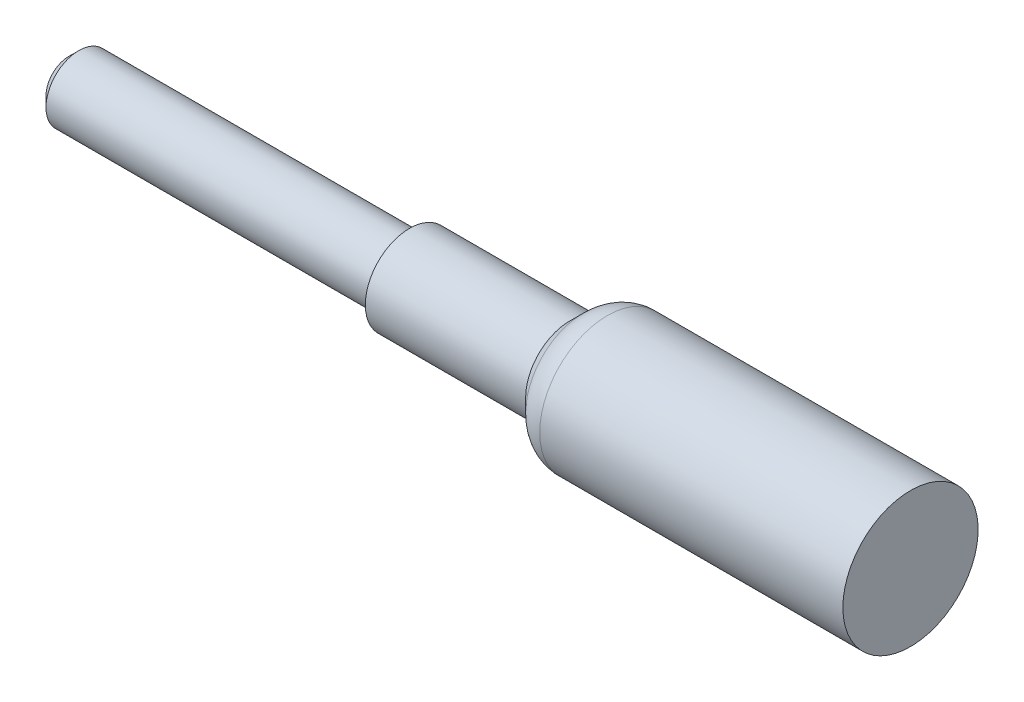
SolidWorks part; units mm, degrees
ref_plane "Front Plane" through (0, 0, 0) normal (0, 0, 1) x (1, 0, 0)
ref_plane "Top Plane" through (0, 0, 0) normal (0, 1, 0) x (1, 0, 0)
ref_plane "Right Plane" through (0, 0, 0) normal (1, 0, 0) x (0, 0, -1)
sketch "Sketch1" plane through (0, 0, 0) normal (0, 0, 1) x (1, 0, 0)
  line L0 (0, 0) -> (63.1616, 0) construction
  line L1 (31.75, 0) -> (31.75, 4.2862)
  line L2 (31.75, 4.2862) -> (11.6462, 4.2862)
  line L3 (11.6462, 4.2862) -> (10.16, 2.8)
  line L4 (10.16, 2.8) -> (0, 2.8)
  line L5 (0, 2.8) -> (0, 0)
  line L6 (0, 0) -> (31.75, 0)
  point P9 (5.08, 2.8)
  dimension "D1" = 8.5725
  dimension "D2" = 5.6
  dimension "D3" = 45
  dimension "D4" = 26.67
  dimension "D5" = 10.16
revolve "Revolve1" add sketch "Sketch1" angle 360 about L0
ref_plane "Plane1" through (5.08, 0, 0) normal (-1, 0, 0) x (0, 0, 1)
sketch "Sketch3" plane through (0, 0, 0) normal (-1, 0, 0) x (0, 0, 1)
  circle A0 centre (0, 0) radius 1.7272
  circle A1 centre (0, 0) radius 2.0828 construction
  dimension "D1" = 3.4544
  dimension "D2" = 4.1656
fillet "Fillet1" radius 2.159 1 edges at (11.6462, 0, 4.2862)
sketch "Sketch6" plane through (0, 0, 0) normal (-1, 0, 0) x (0, 0, 1)
  circle A0 centre (0, 0) radius 2.0828
  dimension "D1" = 4.1656
extrude "Boss-Extrude1" add sketch "Sketch6" along normal blind 21.59
chamfer "Chamfer2" distance 0.635 angle 45 1 edges at (-21.59, 0, 2.0828)
